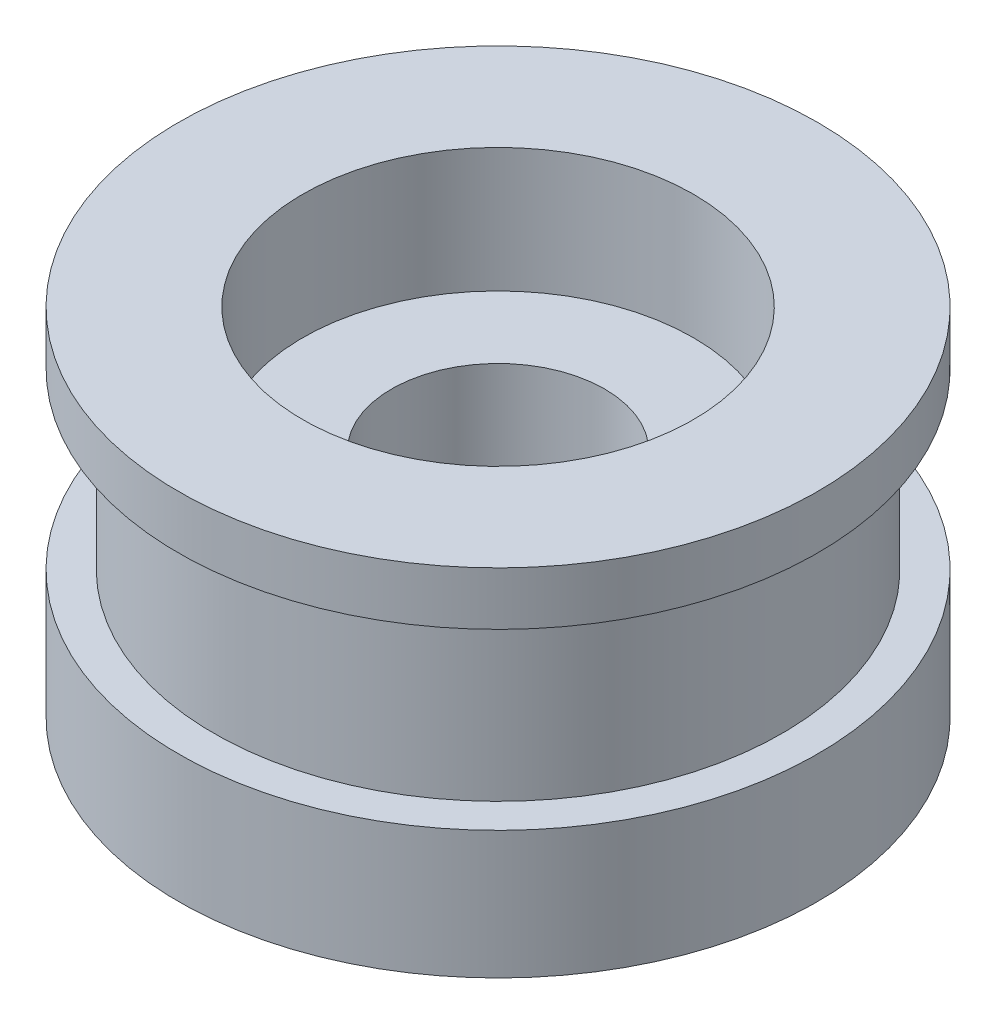
SolidWorks part; units mm, degrees
ref_plane "Front Plane" through (0, 0, 0) normal (0, 0, 1) x (1, 0, 0)
ref_plane "Top Plane" through (0, 0, 0) normal (0, 1, 0) x (1, 0, 0)
ref_plane "Right Plane" through (0, 0, 0) normal (1, 0, 0) x (0, 0, -1)
ref_axis "Axis1" through (0, -50, 0) along (0, 1, 0)
sketch "Sketch1" plane through (0, 0, 0) normal (0, 0, 1) x (1, 0, 0)
  line L0 (1.5, 0) -> (1.5, 3.25)
  line L1 (1.5, 3.25) -> (2.75, 3.25)
  line L2 (2.75, 3.25) -> (2.75, 5)
  line L3 (2.75, 5) -> (4.5, 5)
  line L4 (4.5, 5) -> (4.5, 4.25)
  line L5 (4.5, 4.25) -> (4, 4.25)
  line L6 (4, 4.25) -> (4, 1.8)
  line L7 (4, 1.8) -> (4.5, 1.8)
  line L8 (4.5, 1.8) -> (4.5, 0)
  line L9 (4.5, 0) -> (1.5, 0)
  line L10 (0, -55) -> (0, 55) construction
  line L11 (55, 0) -> (-55, 0) construction
  dimension "D1" = 0.75
  dimension "D2" = 1.8
  dimension "D3" = 5
  dimension "D4" = 1
  dimension "D5" = 1.75
  dimension "D6" = 3
  dimension "D7" = 4.5
  dimension "D8" = 0.5
revolve "Revolve1" add sketch "Sketch1" angle 360 about axis through (0, -50, 0) along (0, 1, 0)
